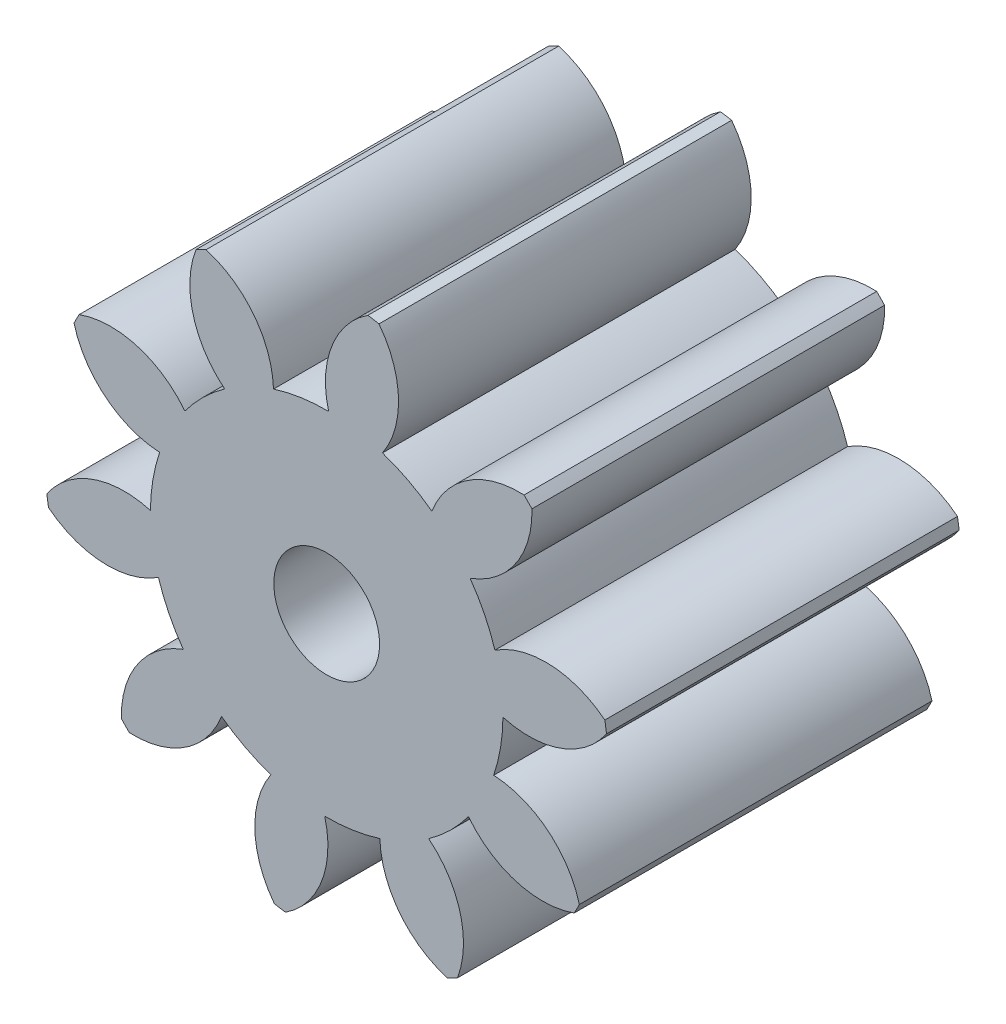
SolidWorks part; units mm, degrees
ref_plane "Front" through (0, 0, 0) normal (0, 0, 1) x (1, 0, 0)
ref_plane "Top" through (0, 0, 0) normal (0, 1, 0) x (1, 0, 0)
ref_plane "Right" through (0, 0, 0) normal (1, 0, 0) x (0, 0, -1)
sketch "Sketch1" plane through (0, 0, 0) normal (0, 0, 1) x (1, 0, 0)
  circle A0 centre (0, 0) radius 0.9
  circle A1 centre (0, 0) radius 6
  dimension "D1" = 1.8
  dimension "D2" = 12
extrude "Boss-Extrude1" add sketch "Sketch1" along normal mid plane 6
other "Freeze***"
sketch "Sketch2" plane through (0, 0, 3) normal (0, 0, 1) x (1, 0, 0)
  circle A0 centre (0, 0) radius 6 construction
  circle A1 centre (0, 0) radius 6
  arc A82 (-0.9043, 2.8594) -> (-2.0525, 4.339) centre (-2.5033, 2.8039) ccw
  arc A83 (-2.0525, 4.339) -> (-2.2243, 4.2535) centre (0, 0) ccw
  arc A84 (-2.2243, 4.2535) -> (-1.7361, 2.4454) centre (-0.7277, 3.6877) ccw
  arc A85 (-1.7361, 2.4454) -> (-2.4123, 1.7818) centre (0, 0) ccw
  arc A86 (-2.4123, 1.7818) -> (-4.2109, 2.3039) centre (-3.6733, 0.7969) ccw
  arc A87 (-4.2109, 2.3039) -> (-4.2997, 2.1337) centre (0, 0) ccw
  arc A88 (-4.2997, 2.1337) -> (-2.8419, 0.9579) centre (-2.7563, 2.5556) ccw
  arc A89 (-2.8419, 0.9579) -> (-2.9989, 0.0236) centre (0, 0) ccw
  arc A90 (-2.9989, 0.0236) -> (-4.7609, -0.6112) centre (-3.4402, -1.5144) ccw
  arc A91 (-4.7609, -0.6112) -> (-4.7327, -0.801) centre (0, 0) ccw
  arc A92 (-4.7327, -0.801) -> (-2.8622, -0.8955) centre (-3.732, 0.4474) ccw
  arc A93 (-2.8622, -0.8955) -> (-2.44, -1.7437) centre (0, 0) ccw
  arc A94 (-2.44, -1.7437) -> (-3.4924, -3.2929) centre (-1.8931, -3.2473) ccw
  arc A95 (-3.4924, -3.2929) -> (-3.358, -3.4299) centre (0, 0) ccw
  arc A96 (-3.358, -3.4299) -> (-1.7892, -2.4068) centre (-3.2823, -1.8317) ccw
  arc A97 (-1.7892, -2.4068) -> (-0.9491, -2.8448) centre (0, 0) ccw
  arc A98 (-0.9491, -2.8448) -> (-0.8899, -4.7168) centre (0.3772, -3.7398) ccw
  arc A99 (-0.8899, -4.7168) -> (-0.7006, -4.7486) centre (0, 0) ccw
  arc A100 (-0.7006, -4.7486) -> (-0.0328, -2.9988) centre (-1.5788, -3.4111) ccw
  arc A101 (-0.0328, -2.9988) -> (0.9043, -2.8594) centre (0, 0) ccw
  arc A102 (0.9043, -2.8594) -> (2.0525, -4.339) centre (2.5033, -2.8039) ccw
  arc A103 (2.0525, -4.339) -> (2.2243, -4.2535) centre (0, 0) ccw
  arc A104 (2.2243, -4.2535) -> (1.7361, -2.4454) centre (0.7277, -3.6877) ccw
  arc A105 (1.7361, -2.4454) -> (2.4123, -1.7818) centre (0, 0) ccw
  arc A106 (2.4123, -1.7818) -> (4.2109, -2.3039) centre (3.6733, -0.7969) ccw
  arc A107 (4.2109, -2.3039) -> (4.2997, -2.1337) centre (0, 0) ccw
  arc A108 (4.2997, -2.1337) -> (2.8419, -0.9579) centre (2.7563, -2.5556) ccw
  arc A109 (2.8419, -0.9579) -> (2.9989, -0.0236) centre (0, 0) ccw
  arc A110 (2.9989, -0.0236) -> (4.7609, 0.6112) centre (3.4402, 1.5144) ccw
  arc A111 (4.7609, 0.6112) -> (4.7327, 0.801) centre (0, 0) ccw
  arc A112 (4.7327, 0.801) -> (2.8622, 0.8955) centre (3.732, -0.4474) ccw
  arc A113 (2.8622, 0.8955) -> (2.44, 1.7437) centre (0, 0) ccw
  arc A114 (2.44, 1.7437) -> (3.4924, 3.2929) centre (1.8931, 3.2473) ccw
  arc A115 (3.4924, 3.2929) -> (3.358, 3.4299) centre (0, 0) ccw
  arc A116 (3.358, 3.4299) -> (1.7892, 2.4068) centre (3.2823, 1.8317) ccw
  arc A117 (1.7892, 2.4068) -> (0.9491, 2.8448) centre (0, 0) ccw
  arc A118 (0.9491, 2.8448) -> (0.8899, 4.7168) centre (-0.3772, 3.7398) ccw
  arc A119 (0.8899, 4.7168) -> (0.7006, 4.7486) centre (0, 0) ccw
  arc A120 (0.7006, 4.7486) -> (0.0328, 2.9988) centre (1.5788, 3.4111) ccw
  arc A121 (0.0328, 2.9988) -> (-0.9043, 2.8594) centre (0, 0) ccw
extrude "Cut-Extrude1" cut sketch "Sketch2" against normal through all
